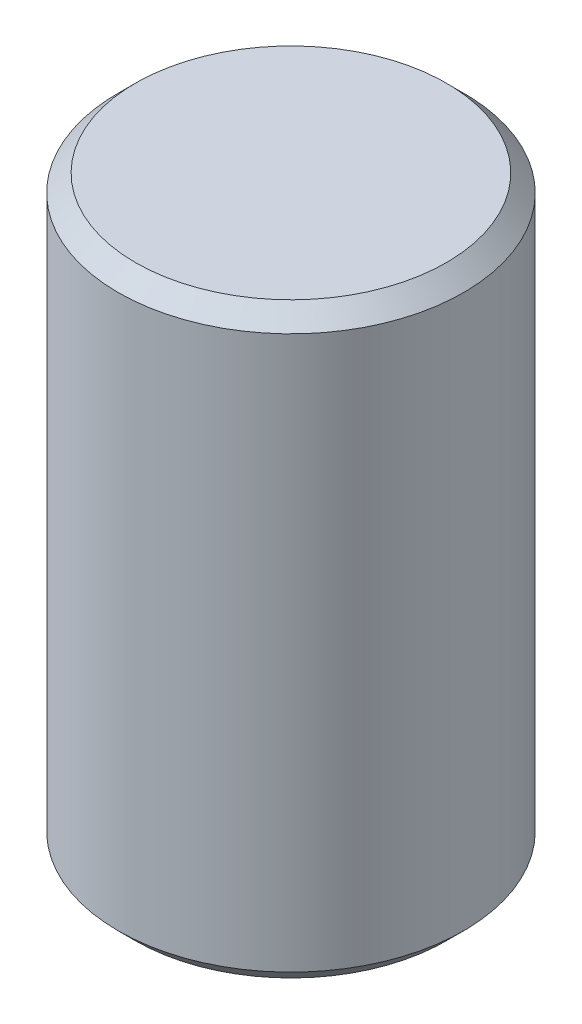
SolidWorks part; units mm, degrees
material "Plain Carbon Steel"
ref_plane "Front Plane" through (0, 0, 0) normal (0, 0, 1) x (1, 0, 0)
ref_plane "Top Plane" through (0, 0, 0) normal (0, 1, 0) x (1, 0, 0)
ref_plane "Right Plane" through (0, 0, 0) normal (1, 0, 0) x (0, 0, -1)
sketch "Sketch1" plane through (0, 0, 0) normal (0, 1, 0) x (1, 0, 0)
  circle A0 centre (0, 0) radius 5
  dimension "D1" = 10
extrude "Boss-Extrude1" add sketch "Sketch1" along normal mid plane 17
chamfer "Chamfer1" distance 0.5 angle 45 2 edges at (0, -8.5, 5) (0, 8.5, 5)
